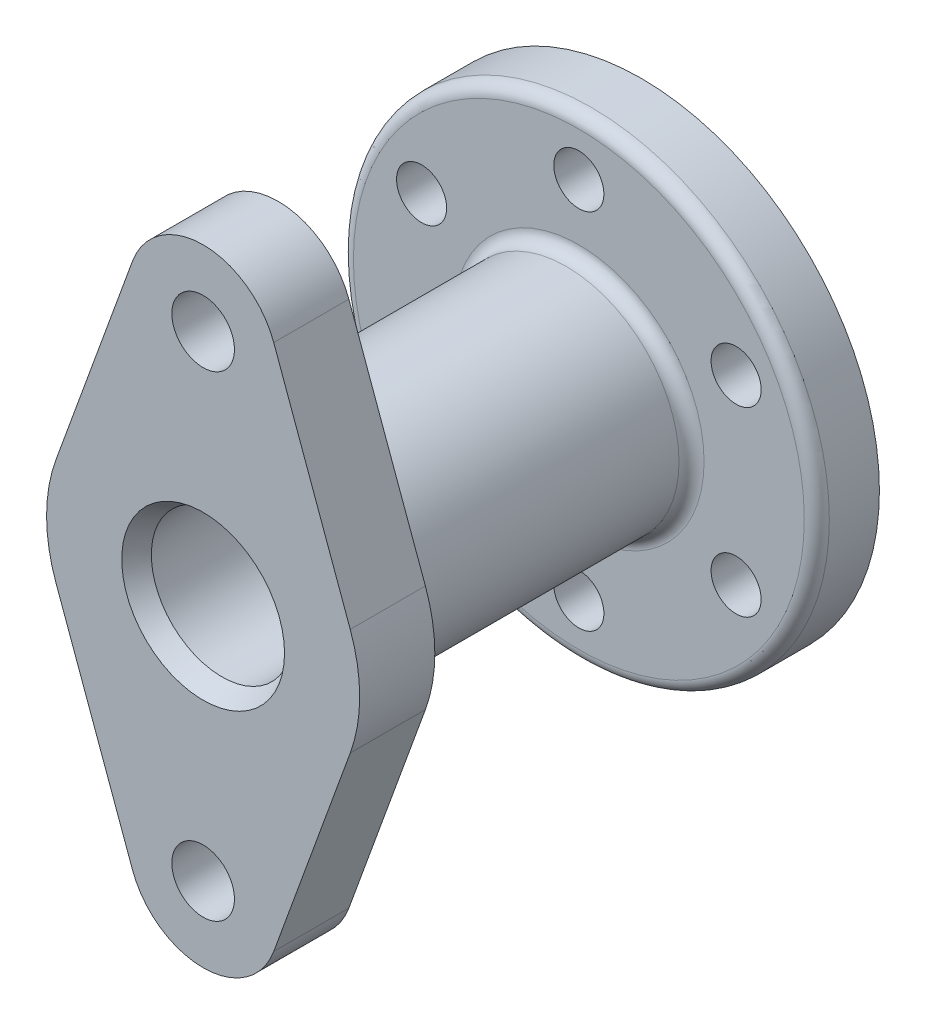
SolidWorks part; units mm, degrees
material "___"
ref_plane "Front Plane" through (0, 0, 0) normal (0, 0, 1) x (1, 0, 0)
ref_plane "Top Plane" through (0, 0, 0) normal (0, 1, 0) x (1, 0, 0)
ref_plane "Right Plane" through (0, 0, 0) normal (1, 0, 0) x (0, 0, -1)
sketch "Sketch1" plane through (0, 0, 0) normal (0, 0, 1) x (1, 0, 0)
  line L0 (-23.4915, 8.5526) -> (-11.2759, 42.1053)
  line L1 (0, 0) -> (25, 0) construction
  line L2 (0, 0) -> (0, 50) construction
  line L3 (23.4915, 8.5526) -> (11.2759, 42.1053)
  line L4 (-23.4915, 8.5526) -> (-11.2759, 42.1053)
  line L5 (23.4915, 8.5526) -> (11.2759, 42.1053)
  line L6 (-23.4915, -8.5526) -> (-11.2759, -42.1053)
  line L7 (23.4915, -8.5526) -> (11.2759, -42.1053)
  line L8 (23.4915, -8.5526) -> (11.2759, -42.1053)
  arc A0 (-23.4915, 8.5526) -> (-23.4915, -8.5526) centre (0, 0) ccw
  circle A1 centre (0, 38) radius 5
  arc A2 (11.2759, 42.1053) -> (-11.2759, 42.1053) centre (0, 38) ccw
  arc A3 (11.2759, -42.1053) -> (-11.2759, -42.1053) centre (0, -38) cw
  circle A4 centre (0, -38) radius 5
  arc A5 (23.4915, -8.5526) -> (23.4915, 8.5526) centre (0, 0) ccw
  point P6 (25, 0)
  dimension "D1" = 50
  dimension "D3" = 24
  dimension "D4" = 10
  dimension "D2" = 38
extrude "Boss-Extrude1" add sketch "Sketch1" along normal mid plane 12 contours L7 A5 L3 A2 L0 A0 L6 A3 A4 A1
sketch "Sketch2" plane through (0, 0, 6) normal (0, 0, 1) x (1, 0, 0)
  circle A0 centre (0, 0) radius 13
  dimension "D1" = 26
extrude "Cut-Extrude1" cut sketch "Sketch2" against normal blind 3 draft 30
sketch "Sketch3" plane through (0, 0, -6) normal (0, 0, -1) x (-1, 0, 0)
  circle A2 centre (0, 0) radius 18
  dimension "D1" = 36
extrude "Boss-Extrude2" add sketch "Sketch3" along normal blind 48
sketch "Sketch4" plane through (0, 0, -54) normal (0, 0, -1) x (-1, 0, 0)
  circle A0 centre (0, 0) radius 38
  dimension "D1" = 76
extrude "Boss-Extrude3" add sketch "Sketch4" along normal blind 10
sketch "Sketch5" plane through (0, 0, 3) normal (0, 0, 1) x (1, 0, 0)
  circle A0 centre (0, 0) radius 11.2679 construction
  circle A1 centre (0, 0) radius 11.2679
extrude "Cut-Extrude2" cut sketch "Sketch5" against normal blind 25
sketch "Sketch6" plane through (0, 0, -22) normal (0, 0, 1) x (1, 0, 0)
  circle A0 centre (0, 0) radius 10
  dimension "D1" = 20
extrude "Cut-Extrude3" cut sketch "Sketch6" against normal through all
sketch "Sketch7" plane through (0, 0, -54) normal (0, 0, 1) x (1, 0, 0)
  circle A0 centre (0, 0) radius 29 construction
  circle A1 centre (0, 29) radius 4
  circle A2 centre (0, 0) radius 29 construction
  circle A3 centre (25.1147, 14.5) radius 4
  circle A4 centre (0, 0) radius 29 construction
  circle A5 centre (25.1147, -14.5) radius 4
  circle A6 centre (0, 0) radius 29 construction
  circle A7 centre (0, -29) radius 4
  circle A8 centre (0, 0) radius 29 construction
  circle A9 centre (-25.1147, -14.5) radius 4
  circle A10 centre (0, 0) radius 29 construction
  circle A11 centre (-25.1147, 14.5) radius 4
  point P22 (0, 0)
  dimension "D1" = 58
  dimension "D2" = 8
  dimension "D3" = 6
extrude "Cut-Extrude4" cut sketch "Sketch7" against normal through all
fillet "Fillet1" radius 2 2 edges at (-38, 0, -54) (-18, 0, -54)
